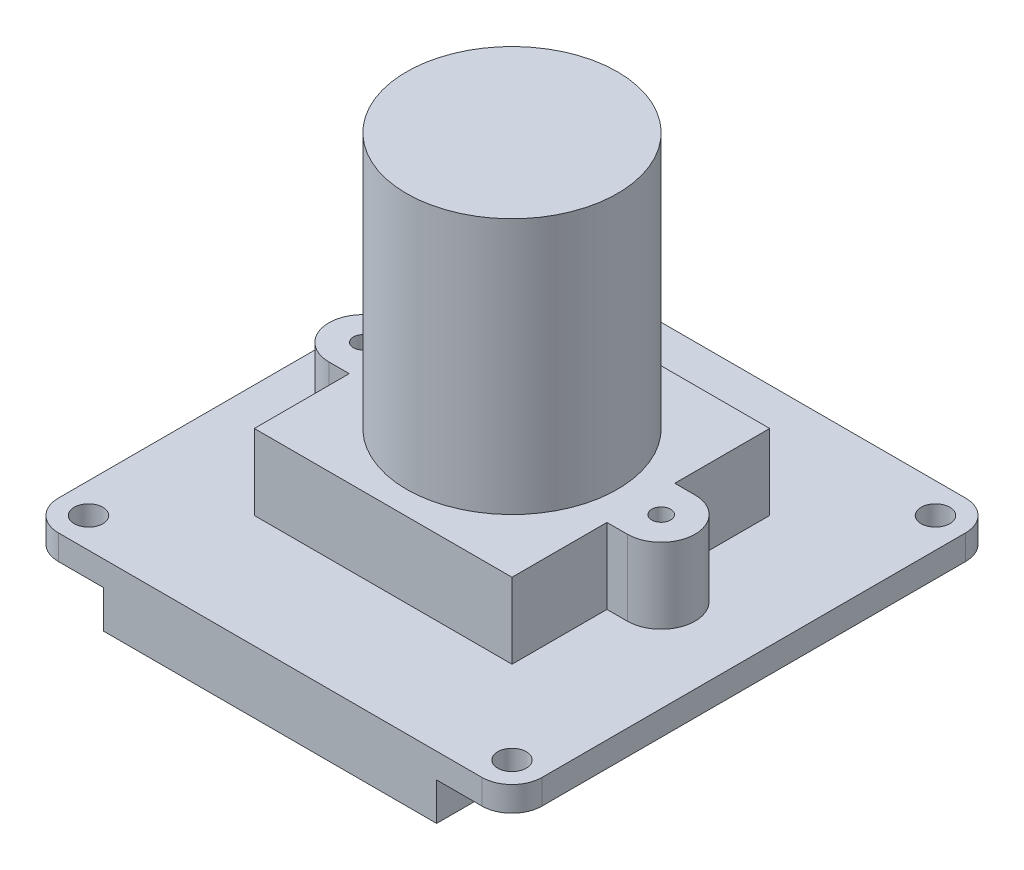
SolidWorks part; units mm, degrees
ref_plane "Front Plane" through (0, 0, 0) normal (0, 0, 1) x (1, 0, 0)
ref_plane "Top Plane" through (0, 0, 0) normal (0, 1, 0) x (1, 0, 0)
ref_plane "Right Plane" through (0, 0, 0) normal (1, 0, 0) x (0, 0, -1)
sketch "Sketch1" plane through (0, 0, 0) normal (0, 1, 0) x (1, 0, 0)
  line L0 (0, 0) -> (0, 16.05) construction
  line L1 (-16.05, 16.05) -> (16.05, 16.05)
  line L2 (-16.05, 16.05) -> (-16.05, -16.05)
  line L3 (-16.05, -16.05) -> (16.05, -16.05)
  line L4 (16.05, 16.05) -> (16.05, -16.05)
  line L5 (0, 0) -> (-16.05, 0) construction
  line L6 (-14.05, 13.1) -> (-14.05, -13.1) construction
  line L7 (-13.1, 14.05) -> (13.1, 14.05) construction
  circle A0 centre (-14.05, 14.05) radius 0.95
  circle A1 centre (14.05, 14.05) radius 0.95
  circle A2 centre (14.05, -14.05) radius 0.95
  circle A3 centre (-14.05, -14.05) radius 0.95
  point P4 (0, 16.05)
  point P6 (-16.05, 0)
  point P20 (-8.025, 0)
  point P23 (0, 8.025)
  dimension "D2" = 1.9
  dimension "D1" = 32.1
  dimension "D3" = 26.2
extrude "Boss-Extrude1" add sketch "Sketch1" along normal blind 1.65
sketch "Sketch2" plane through (0, 0, 0) normal (0, -1, 0) x (1, 0, 0)
  line L0 (-16.05, 16.05) -> (16.05, 16.05) construction
  line L1 (-11.05, 16.05) -> (11.05, 16.05)
  line L2 (-11.05, 16.05) -> (-11.05, 9.3)
  line L3 (-11.05, 9.3) -> (11.05, 9.3)
  line L4 (11.05, 16.05) -> (11.05, 9.3)
  point P6 (0, 9.3)
  dimension "D1" = 6.75
  dimension "D2" = 5
extrude "Boss-Extrude2" add sketch "Sketch2" along normal blind 2.5
sketch "Sketch3" plane through (0, 1.65, 0) normal (0, 1, 0) x (1, 0, 0)
  line L0 (9.9, 2.25) -> (8.55, 2.25)
  line L1 (-8.55, 8.55) -> (8.55, 8.55)
  line L3 (-8.55, -8.55) -> (8.55, -8.55)
  line L5 (9.9, -2.25) -> (8.55, -2.25)
  line L6 (8.55, 8.55) -> (8.55, 2.25)
  line L7 (8.55, -2.25) -> (8.55, -8.55)
  line L8 (0, 8.55) -> (0, 0) construction
  line L9 (-8.55, -2.25) -> (-8.55, -8.55)
  line L10 (-8.55, 8.55) -> (-8.55, 2.25)
  line L11 (-9.9, -2.25) -> (-8.55, -2.25)
  line L12 (-9.9, 2.25) -> (-8.55, 2.25)
  line L13 (-8.55, 8.55) -> (-8.55, -8.55) construction
  arc A0 (9.9, 2.25) -> (9.9, -2.25) centre (9.9, 0) cw
  circle A1 centre (9.9, 0) radius 0.625
  circle A2 centre (-9.9, 0) radius 0.625
  arc A3 (-9.9, 2.25) -> (-9.9, -2.25) centre (-9.9, 0) ccw
  point P4 (0, 8.55)
  point P15 (12.15, 0)
  point P21 (-8.55, 0)
  dimension "D2" = 1.25
  dimension "D1" = 17.1
  dimension "D3" = 4.5
  dimension "D4" = 3.6
extrude "Boss-Extrude3" add sketch "Sketch3" along normal blind 5
sketch "Sketch4" plane through (0, 6.65, 0) normal (0, 1, 0) x (1, 0, 0)
  circle A0 centre (0, 0) radius 7
  dimension "D1" = 14
extrude "Boss-Extrude4" add sketch "Sketch4" along normal blind 17
fillet "Fillet1" radius 2 4 edges at (16.05, 0.825, -16.05) (16.05, 0.825, 16.05) (-16.05, 0.825, 16.05) (-16.05, 0.825, -16.05)
